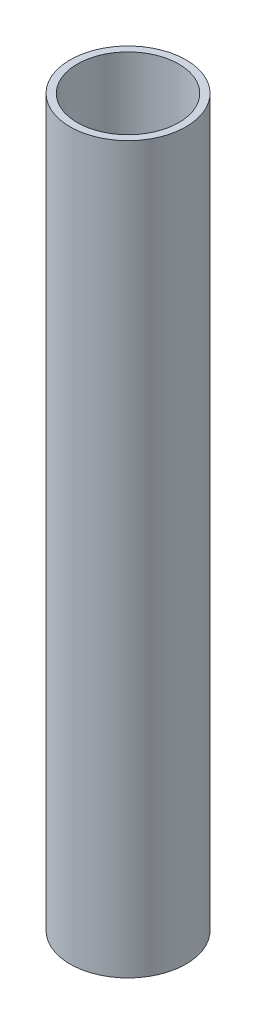
SolidWorks part; units mm, degrees
ref_plane "Front Plane" through (0, 0, 0) normal (0, 0, 1) x (1, 0, 0)
ref_plane "Top Plane" through (0, 0, 0) normal (0, 1, 0) x (1, 0, 0)
ref_plane "Right Plane" through (0, 0, 0) normal (1, 0, 0) x (0, 0, -1)
sketch "Sketch1" plane through (0, -17.7702, 0) normal (0, -1, 0) x (1, 0, 0)
  circle A0 centre (27.5925, 175.6733) radius 8
  circle A1 centre (27.5925, 175.6733) radius 7
extrude "Boss-Extrude1" add sketch "Sketch1" along normal blind 100
